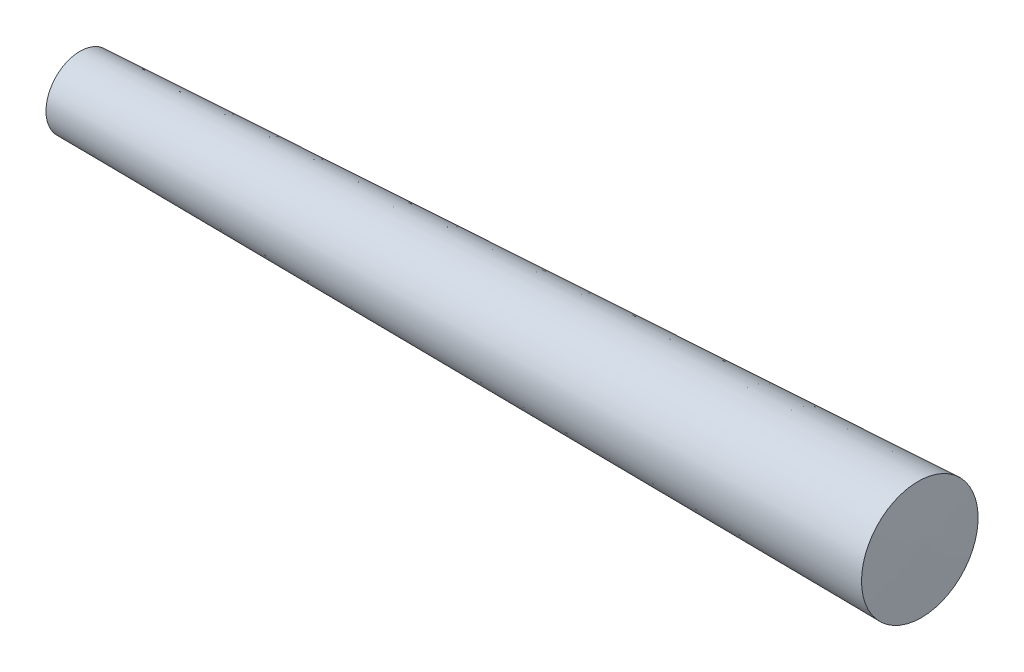
SolidWorks part; units mm, degrees
ref_plane "Front Plane" through (0, 0, 0) normal (0, 0, 1) x (1, 0, 0)
ref_plane "Top Plane" through (0, 0, 0) normal (0, 1, 0) x (1, 0, 0)
ref_plane "Right Plane" through (0, 0, 0) normal (1, 0, 0) x (0, 0, -1)
sketch "Sketch1" plane through (0, 0, 0) normal (0, 0, 1) x (1, 0, 0)
  line L0 (0, 0) -> (36, 0)
  line L1 (0, 0) -> (0, 1.5)
  line L2 (36, 0) -> (36, 2.5)
  line L3 (0, 1.5) -> (36, 2.5)
  dimension "D1" = 36
  dimension "D2" = 1.5
  dimension "D3" = 2.5
revolve "Revolve1" add sketch "Sketch1" angle 360 about L3
